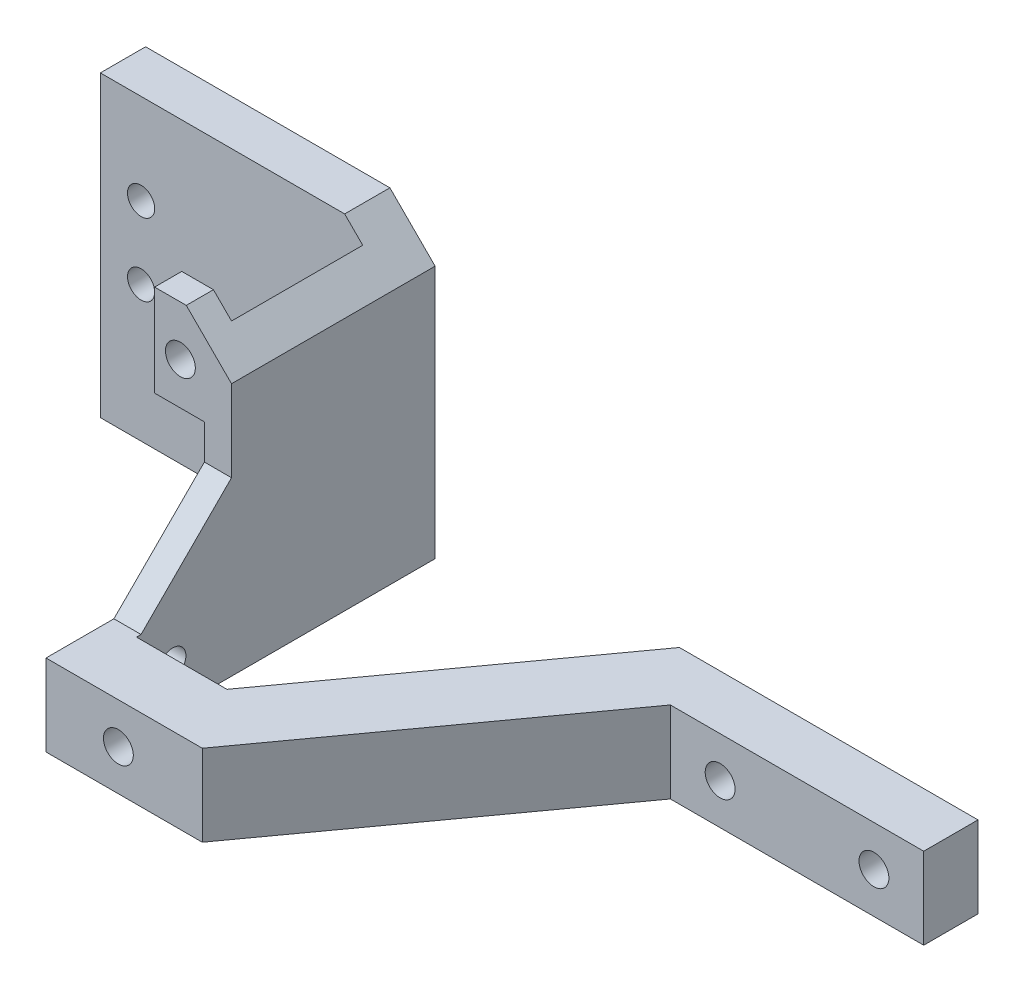
SolidWorks part; units mm, degrees
ref_plane "Płaszczyzna przednia" through (0, 0, 0) normal (0, 0, 1) x (1, 0, 0)
ref_plane "Płaszczyzna górna" through (0, 0, 0) normal (0, 1, 0) x (1, 0, 0)
ref_plane "Płaszczyzna prawa" through (0, 0, 0) normal (1, 0, 0) x (0, 0, -1)
sketch "Szkic1" plane through (0, 0, 0) normal (0, 0, 1) x (1, 0, 0)
  line L0 (0, 0) -> (28, 0)
  line L1 (28, 0) -> (28, 9)
  line L2 (28, 9) -> (0, 9)
  line L3 (0, 9) -> (0, 0)
  line L4 (0, 4.5) -> (28, 4.5) construction
  circle A0 centre (5.5, 4.5) radius 1.65
  circle A1 centre (22.5, 4.5) radius 1.65
  dimension "D3" = 17
  dimension "D1" = 28
  dimension "D2" = 9
  dimension "D4" = 5.5
extrude "Dodanie-wyciągnięcie1" add sketch "Szkic1" along normal blind 6
sketch "Szkic2" plane through (0, 0, 0) normal (0, -1, 0) x (1, 0, 0)
  line L0 (0, 0) -> (-5, 0)
  line L1 (-5, 0) -> (-26, 29.009)
  line L2 (-26, 29.009) -> (-36, 29.009)
  line L3 (-36, 29.009) -> (-36, 36.009)
  line L4 (-36, 36.009) -> (-21.7239, 36.009)
  line L5 (-21.7239, 36.009) -> (0, 6)
  line L6 (0, 6) -> (0, 0)
  dimension "D1" = 21
  dimension "D2" = 7
  dimension "D3" = 5
  dimension "D4" = 10
  dimension "D5" = 14.2761
extrude "Dodanie-wyciągnięcie2" add sketch "Szkic2" against normal up to surface (9 mm away) up to face at (14, 9, 3)
sketch "Szkic3" plane through (0, 0, 0) normal (0, -1, 0) x (1, 0, 0)
  line L0 (-5, 0) -> (28, 0) construction
  line L1 (-36, 36.009) -> (-39, 36.009)
  line L2 (-36, 36.009) -> (-36, -4)
  line L3 (-36, -4) -> (-39, -4)
  line L4 (-39, 36.009) -> (-39, -4)
  dimension "D1" = 3
  dimension "D2" = 4
extrude "Dodanie-wyciągnięcie3" add sketch "Szkic3" against normal up to surface (9 mm away) up to face at (-8.5905, 9, 17.7545)
sketch "Szkic10" plane through (0, 0, 36.009) normal (0, 0, 1) x (1, 0, 0)
  line L0 (-39, 4.5) -> (-21.7239, 4.5) construction
  line L1 (-39, 9) -> (-39, 0) construction
  line L2 (-21.7239, 9) -> (-21.7239, 0) construction
  circle A0 centre (-31, 4.5) radius 1.65
  dimension "D1" = 8
extrude "Wytnij-wyciągnięcie4" cut sketch "Szkic10" against normal up to surface (7 mm away) up to face at (-31, 4.5, 29.009)
sketch "Szkic11" plane through (0, 0, -4) normal (0, 0, -1) x (-1, 0, 0)
  line L0 (36, 9) -> (36, 0) construction
  line L1 (39, 0) -> (36, 0) construction
  line L3 (36, 0) -> (68, 0)
  line L4 (36, 0) -> (36, 33)
  line L5 (36, 33) -> (68, 33)
  line L6 (68, 0) -> (68, 33)
  circle A0 centre (63.5, 15) radius 1.5
  dimension "D2" = 3
  dimension "D1" = 26
  dimension "D3" = 15
  dimension "D4" = 33
  dimension "D5" = 32
extrude "Dodanie-wyciągnięcie4" add sketch "Szkic11" against normal blind 5
sketch "Szkic12" plane through (0, 9, 0) normal (0, 1, 0) x (1, 0, 0)
  line L0 (-39, -1) -> (-39, -36.009) construction
  line L1 (-36, -1) -> (-39, -1)
  line L2 (-36, -1) -> (-36, -18.5045)
  line L3 (-36, -18.5045) -> (-39, -18.5045)
  line L4 (-39, -1) -> (-39, -18.5045)
  line L5 (-68, 4) -> (-36, 4) construction
  dimension "D1" = 22.5045
extrude "Dodanie-wyciągnięcie5" add sketch "Szkic12" along normal up to surface (24 mm away) up to face at (-52, 33, -1.5)
sketch "Szkic13" plane through (0, 33, 0) normal (0, 1, 0) x (1, 0, 0)
  line L1 (-36, -18.5045) -> (-46, -18.5045)
  line L2 (-36, -18.5045) -> (-36, -15.5045)
  line L3 (-36, -15.5045) -> (-46, -15.5045)
  line L4 (-46, -18.5045) -> (-46, -15.5045)
  dimension "D1" = 10
  dimension "D2" = 3
extrude "Dodanie-wyciągnięcie6" add sketch "Szkic13" against normal up to surface (33 mm away) contours L3 L4 L1 L2 up to face at (-23.5603, 0, 11.3363)
sketch "Szkic14" plane through (0, 0, 18.5045) normal (0, 0, 1) x (1, 0, 0)
  line L0 (-46, 33) -> (-36, 33) construction
  line L2 (-36, 33) -> (-36, 9) construction
  circle A0 centre (-41.65, 27.5) radius 1.65
  dimension "D1" = 3.3
  dimension "D2" = 5.5
  dimension "D3" = 4
extrude "Wytnij-wyciągnięcie5" cut sketch "Szkic14" against normal up to surface (3 mm away) up to face at (-42.5, 16.5, 15.5045)
sketch "Szkic15" plane through (0, 0, 18.5045) normal (0, 0, 1) x (1, 0, 0)
  line L1 (-46, 0) -> (-39, 0)
  line L2 (-46, 0) -> (-46, 22.85)
  line L3 (-46, 22.85) -> (-39, 22.85)
  line L4 (-39, 0) -> (-39, 22.85)
  circle A0 centre (-41.65, 27.5) radius 1.65 construction
  dimension "D1" = 3
extrude "Wytnij-wyciągnięcie6" cut sketch "Szkic15" against normal up to surface (3 mm away) up to face at (-43.3, 27.5, 15.5045)
chamfer "Sfazowanie1" distance 10 angle 45 1 edges at (-37.5, 9, 18.5045)
sketch "Szkic16" plane through (0, 0, 1) normal (0, 0, 1) x (1, 0, 0)
  line L0 (-63.5, 15) -> (-63.5, 26.8751) construction
  circle A0 centre (-63.5, 23) radius 1.5
  dimension "D1" = 3
  dimension "D2" = 8
extrude "Wytnij-wyciągnięcie7" cut sketch "Szkic16" against normal up to surface (5 mm away) contours A0 up to face at (-52, 16.5, -4)
sketch "Szkic17" plane through (-39, 0, 0) normal (-1, 0, 0) x (0, 0, 1)
  line L0 (36.009, 0) -> (1, 0) construction
  line L1 (29.009, 9) -> (29.009, 0) construction
  circle A0 centre (25.009, 4.5) radius 1.4629
  dimension "D1" = 4.5
  dimension "D2" = 4
extrude "Wytnij-wyciągnięcie8" cut sketch "Szkic17" against normal up to surface (3 mm away) up to face at (-36, 14.7143, 16.5045)
sketch "Szkic18" plane through (-46, 0, 0) normal (-1, 0, 0) x (0, 0, 1)
  line L1 (15.5045, 33) -> (18.5045, 33)
  line L2 (15.5045, 33) -> (15.5045, 22.85)
  line L3 (15.5045, 22.85) -> (18.5045, 22.85)
  line L4 (18.5045, 33) -> (18.5045, 22.85)
extrude "Wytnij-wyciągnięcie9" cut sketch "Szkic18" against normal blind 1.5
sketch "Szkic19" plane through (0, 0, -4) normal (0, 0, -1) x (-1, 0, 0)
  line L0 (36, 28) -> (41, 33)
  line L1 (36, 33) -> (36, 0) construction
  line L2 (68, 33) -> (36, 33) construction
  line L3 (41, 33) -> (36, 33)
  line L4 (36, 33) -> (36, 28)
  dimension "D1" = 5
  dimension "D2" = 5
extrude "Wytnij-wyciągnięcie10" cut sketch "Szkic19" against normal up to surface (22.5045 mm away) up to face at (-40, 27.5, 18.5045)
